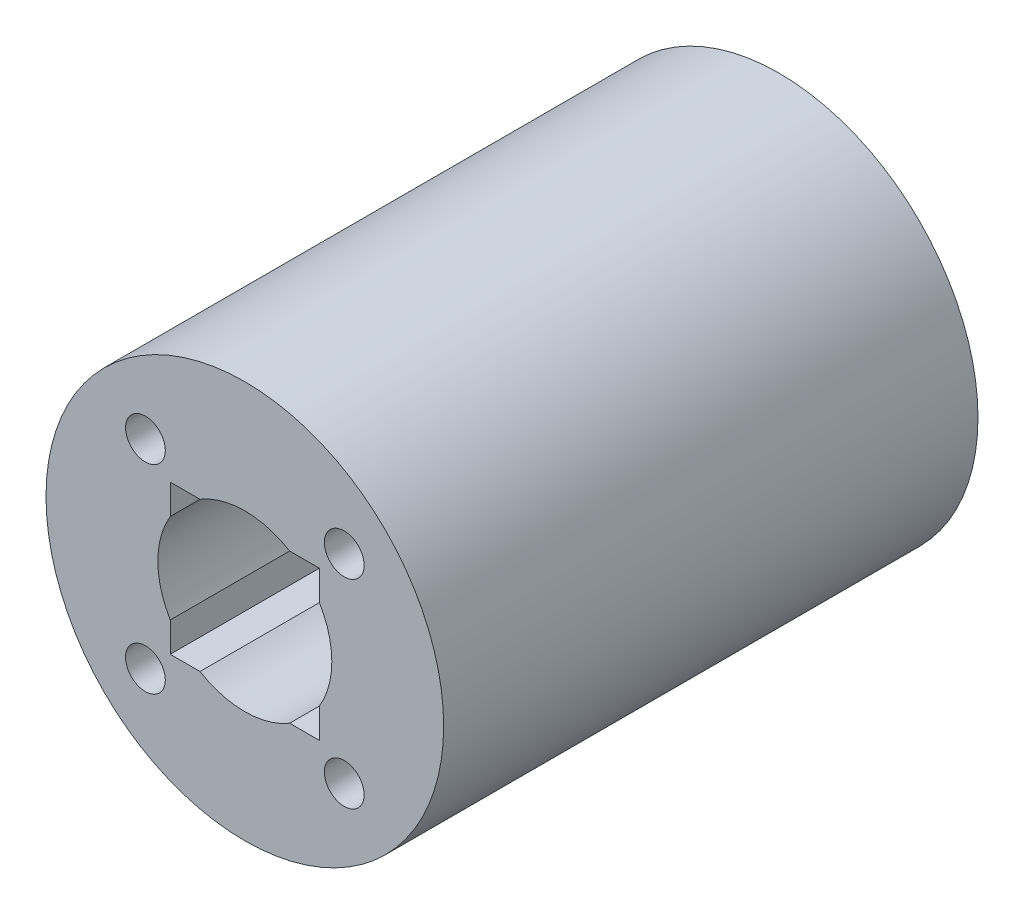
SolidWorks part; units mm, degrees
ref_plane "Front Plane" through (0, 0, 0) normal (0, 0, 1) x (1, 0, 0)
ref_plane "Top Plane" through (0, 0, 0) normal (0, 1, 0) x (1, 0, 0)
ref_plane "Right Plane" through (0, 0, 0) normal (1, 0, 0) x (0, 0, -1)
sketch "Sketch1" plane through (0, 0, 0) normal (0, 0, 1) x (1, 0, 0)
  line L1 (-8, -8) -> (8, -8) construction
  line L2 (-8, -8) -> (-8, 8) construction
  line L3 (-8, 8) -> (8, 8) construction
  line L4 (8, -8) -> (8, 8) construction
  line L5 (-8, -8) -> (8, 8) construction
  line L6 (-8, 8) -> (8, -8) construction
  line L7 (-6, -6) -> (6, -6)
  line L8 (-6, -6) -> (-6, 6)
  line L9 (-6, 6) -> (6, 6)
  line L10 (6, -6) -> (6, 6)
  line L11 (-6, -6) -> (6, 6) construction
  line L12 (-6, 6) -> (6, -6) construction
  circle A0 centre (0, 0) radius 16
  circle A1 centre (-8, 8) radius 1.6
  circle A2 centre (0, 0) radius 11.3137 construction
  circle A3 centre (8, 8) radius 1.6
  circle A4 centre (0, 0) radius 11.3137 construction
  circle A5 centre (8, -8) radius 1.6
  circle A6 centre (0, 0) radius 11.3137 construction
  circle A7 centre (-8, -8) radius 1.6
  circle A8 centre (0, 0) radius 11.3137 construction
  circle A9 centre (0, 0) radius 7
  dimension "D1" = 32
  dimension "D4" = 3.2
  dimension "D6" = 14
  dimension "D2" = 16
  dimension "D5" = 12
  dimension "D3" = 4
extrude "Boss-Extrude1" add sketch "Sketch1" along normal blind 43 contours A0 A9 L9 L10 L7 L8 A7 A5 A3 A1
